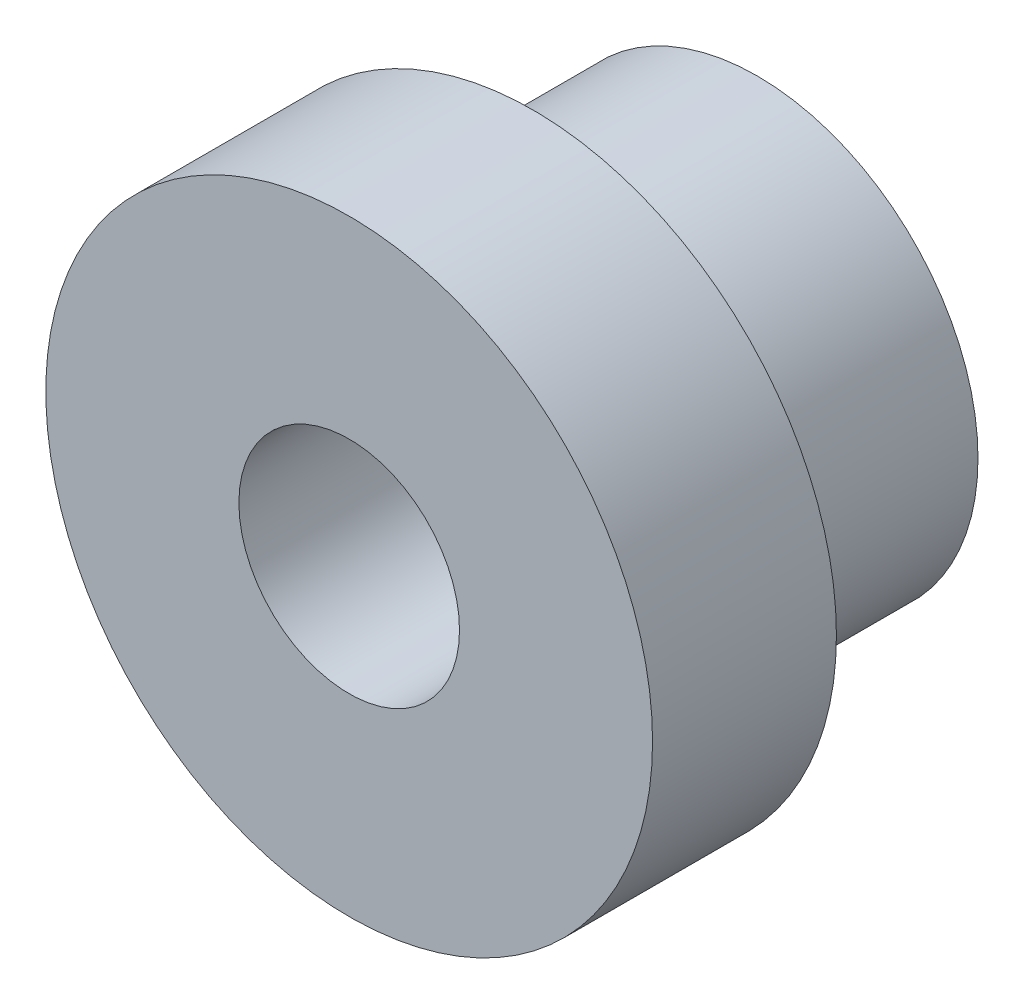
SolidWorks part; units mm, degrees
ref_plane "Ön Düzlem" through (0, 0, 0) normal (0, 0, 1) x (1, 0, 0)
ref_plane "Üst Düzlem" through (0, 0, 0) normal (0, 1, 0) x (1, 0, 0)
ref_plane "Sağ Düzlem" through (0, 0, 0) normal (1, 0, 0) x (0, 0, -1)
sketch "Çizim1" plane through (0, 0, 0) normal (0, 0, 1) x (1, 0, 0)
  circle A0 centre (0, 0) radius 6
  circle A1 centre (0, 0) radius 3
extrude "Yükseklik-Ekstrüzyon1" add sketch "Çizim1" along normal blind 11.1
sketch "Çizim2" plane through (0, 0, 11.1) normal (0, 0, 1) x (1, 0, 0)
  circle A0 centre (0, 0) radius 8.25
  circle A1 centre (0, 0) radius 3
extrude "Yükseklik-Ekstrüzyon2" add sketch "Çizim2" against normal blind 5
